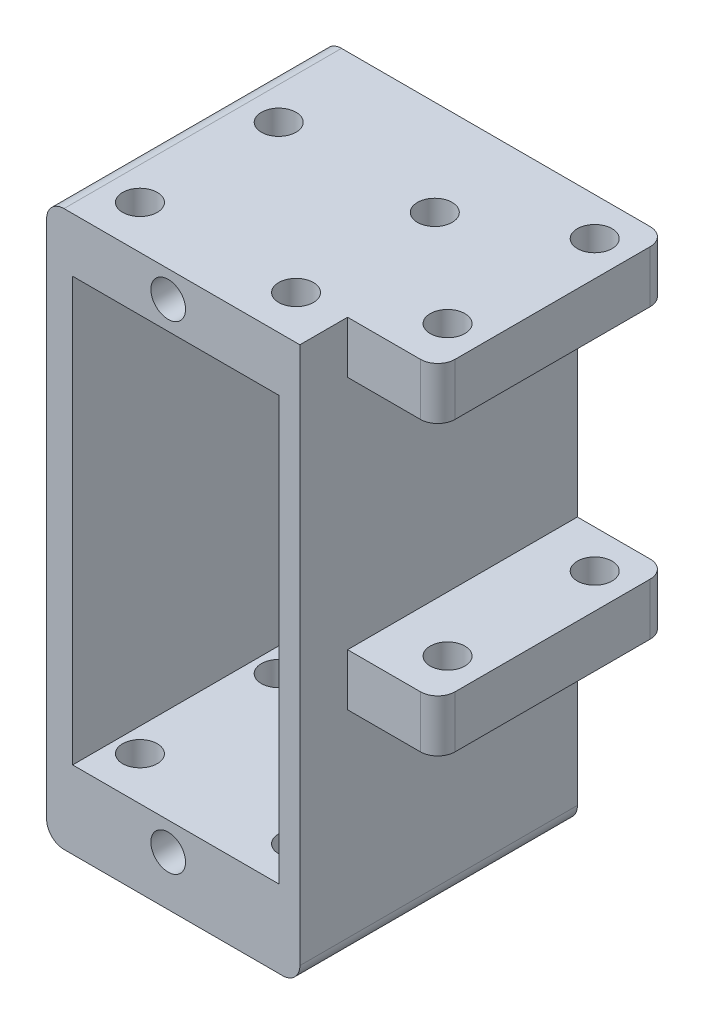
SolidWorks part; units mm, degrees
ref_plane "Front Plane" through (0, 0, 0) normal (0, 0, 1) x (1, 0, 0)
ref_plane "Top Plane" through (0, 0, 0) normal (0, 1, 0) x (1, 0, 0)
ref_plane "Right Plane" through (0, 0, 0) normal (1, 0, 0) x (0, 0, -1)
other "Graphic1"
sketch "Sketch2" plane through (0, 0, 0) normal (0, 0, 1) x (1, 0, 0)
  line L1 (-106.7177, 235.3278) -> (-92.1177, 235.3278)
  line L2 (-106.7177, 235.3278) -> (-106.7177, 203.3278)
  line L3 (-106.7177, 203.3278) -> (-92.1177, 203.3278)
  line L4 (-92.1177, 235.3278) -> (-92.1177, 203.3278)
  dimension "D1" = 14.6
  dimension "D2" = 32
extrude "Boss-Extrude1" add sketch "Sketch2" along normal blind 16
fillet "Fillet1" radius 1 3 edges at (-92.1177, 203.3278, 8) (-106.7177, 203.3278, 8) (-106.7177, 235.3278, 8)
sketch "Sketch3" plane through (0, 0, 16) normal (0, 0, 1) x (1, 0, 0)
  line L0 (-92.1177, 204.3278) -> (-92.1177, 235.3278) construction
  line L3 (-105.2177, 232.2) -> (-93.3177, 232.2)
  line L4 (-105.2177, 232.2) -> (-105.2177, 207.8)
  line L5 (-105.2177, 207.8) -> (-93.3177, 207.8)
  line L6 (-93.3177, 232.2) -> (-93.3177, 207.8)
  dimension "D1" = 11.9
  dimension "D2" = 24.4
  dimension "D3" = 1.2
extrude "Cut-Extrude1" cut sketch "Sketch3" against normal blind 16
sketch "Sketch4" plane through (0, 0, 16) normal (0, 0, 1) x (1, 0, 0)
  line L0 (-93.3177, 232.2) -> (-105.2177, 232.2) construction
  line L1 (-105.2177, 207.8) -> (-93.3177, 207.8) construction
  circle A0 centre (-99.7091, 233.8) radius 1
  circle A1 centre (-99.7091, 206.2) radius 1
  dimension "D1" = 1.6
  dimension "D2" = 1.6
extrude "Cut-Extrude2" cut sketch "Sketch4" against normal blind 16
sketch "Sketch5" plane through (0, 235.3278, 0) normal (0, 1, 0) x (1, 0, 0)
  line L1 (-103.8376, -5.5) -> (-103.8376, -13.5) construction
  circle A0 centre (-103.8376, -5.5) radius 1
  circle A1 centre (-94.8376, -5.5) radius 1
  circle A2 centre (-94.8376, -13.5) radius 1
  circle A3 centre (-103.8376, -13.5) radius 1
  dimension "D1" = 2
  dimension "D3" = 8
  dimension "D2" = 2
extrude "Cut-Extrude3" cut sketch "Sketch5" against normal through all
other "Graphic2"
sketch "Sketch6" plane through (0, 235.3278, 0) normal (0, 1, 0) x (1, 0, 0)
  line L1 (-92.1177, 0) -> (-86.9177, 0)
  line L2 (-92.1177, 0) -> (-92.1177, -13.25)
  line L3 (-92.1177, -13.25) -> (-86.9177, -13.25)
  line L4 (-86.9177, 0) -> (-86.9177, -13.25)
  dimension "D1" = 5.2
  dimension "D2" = 13.25
extrude "Boss-Extrude2" add sketch "Sketch6" against normal blind 3
ref_plane "Plane1" through (0, 218.7278, 0) normal (0, 1, 0) x (1, 0, 0)
sketch "Sketch7" plane through (0, 218.7278, 0) normal (0, 1, 0) x (1, 0, 0)
  line L1 (-92.1177, 0) -> (-86.9177, 0)
  line L2 (-92.1177, 0) -> (-92.1177, -13.25)
  line L3 (-92.1177, -13.25) -> (-86.9177, -13.25)
  line L4 (-86.9177, 0) -> (-86.9177, -13.25)
  dimension "D1" = 5.2
  dimension "D2" = 13.25
extrude "Boss-Extrude3" add sketch "Sketch7" against normal blind 3
sketch "Sketch8" plane through (0, 235.3278, 0) normal (0, 1, 0) x (1, 0, 0)
  line L0 (-86.9177, 0) -> (-105.7177, 0) construction
  line L2 (-86.9177, -13.25) -> (-86.9177, 0) construction
  line L3 (-88.9177, -2.2) -> (-88.9177, -15.5853) construction
  circle A0 centre (-88.9177, -2.2) radius 1
  circle A1 centre (-88.9177, -10.6845) radius 1
  dimension "D1" = 2.2
  dimension "D2" = 2
extrude "Cut-Extrude4" cut sketch "Sketch8" against normal blind 33
fillet "Fillet2" radius 1 4 edges at (-86.9177, 233.8278, 13.25) (-86.9177, 217.2278, 13.25) (-86.9177, 217.2278, 0) (-86.9177, 233.8278, 0)
